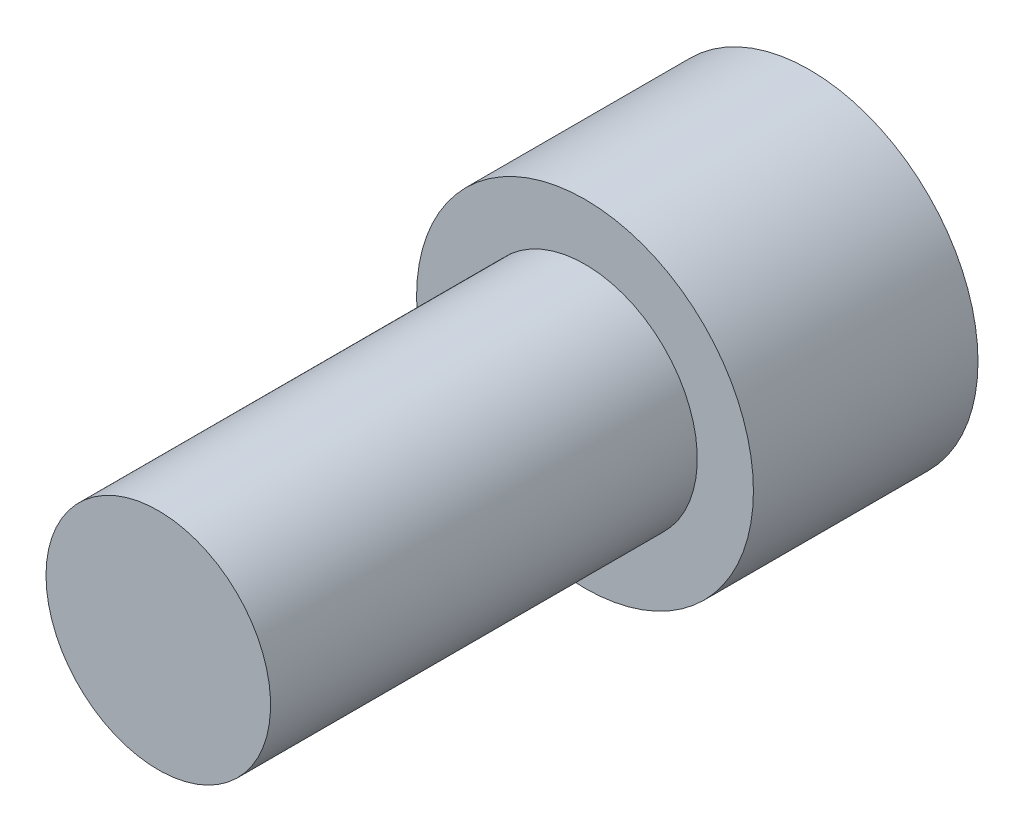
SolidWorks part; units mm, degrees
ref_plane "Ön Düzlem" through (0, 0, 0) normal (0, 0, 1) x (1, 0, 0)
ref_plane "Üst Düzlem" through (0, 0, 0) normal (0, 1, 0) x (1, 0, 0)
ref_plane "Sağ Düzlem" through (0, 0, 0) normal (1, 0, 0) x (0, 0, -1)
sketch "Sketch1" plane through (0, 0, 0) normal (0, 0, 1) x (1, 0, 0)
  circle A0 centre (0, 0) radius 7.5
  dimension "D1" = 15
extrude "Boss-Extrude1" add sketch "Sketch1" along normal blind 250
sketch "Sketch2" plane through (0, 0, 0) normal (0, 0, 1) x (1, 0, 0)
  circle A0 centre (0, 0) radius 5
  dimension "D1" = 10
extrude "Cut-Extrude1" cut sketch "Sketch2" along normal blind 10
ref_plane "Plane1" through (0, 0, 20) normal (0, 0, -1) x (-1, 0, 0)
sketch "Sketch3" plane through (0, 0, 10) normal (0, 0, -1) x (-1, 0, 0)
  circle A0 centre (0, 0) radius 5
  circle A1 centre (0, 0) radius 9.435
extrude "Cut-Extrude2" cut sketch "Sketch3" against normal blind 19
sketch "Sketch5" plane through (0, 0, 29) normal (0, 0, -1) x (-1, 0, 0)
  circle A0 centre (0, 0) radius 25.7657
extrude "Cut-Extrude3" cut sketch "Sketch5" against normal up to surface (221 mm away) up to face at (7.5, 0, 250)
